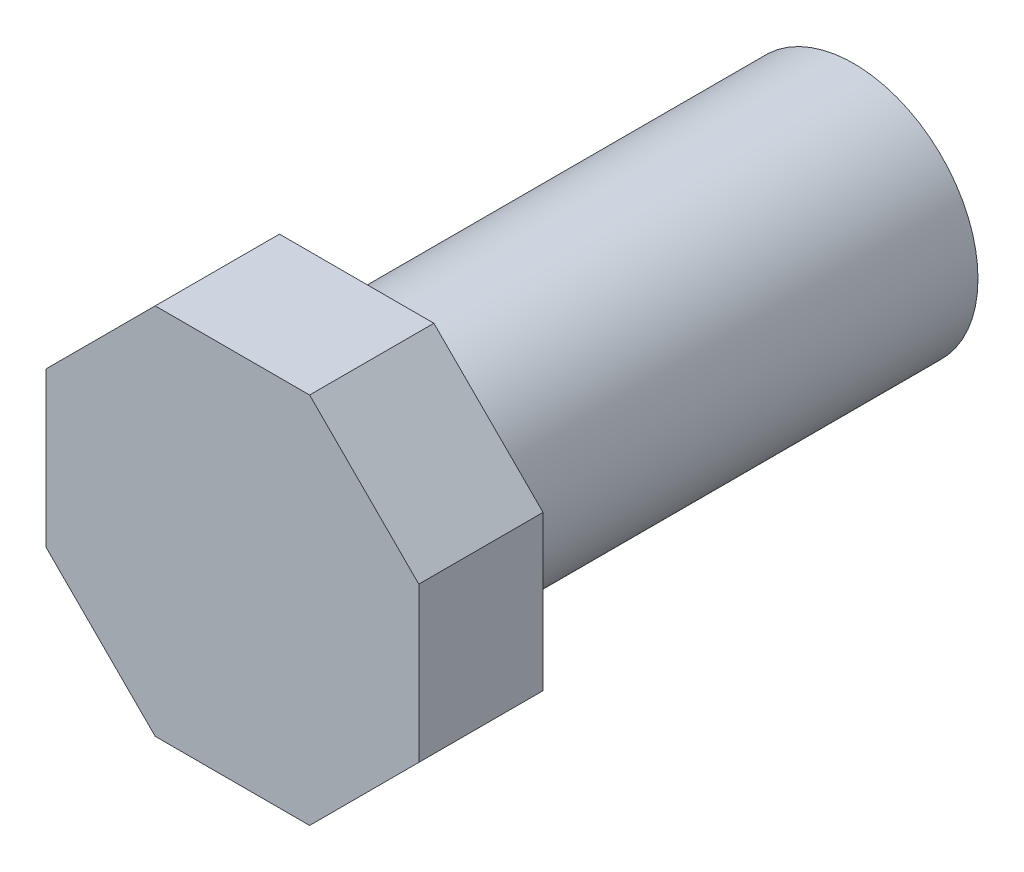
SolidWorks part; units mm, degrees
ref_plane "Plan de face" through (0, 0, 0) normal (0, 0, 1) x (1, 0, 0)
ref_plane "Plan de dessus" through (0, 0, 0) normal (0, 1, 0) x (1, 0, 0)
ref_plane "Plan de droite" through (0, 0, 0) normal (1, 0, 0) x (0, 0, -1)
sketch "Esquisse1" plane through (0, 0, 0) normal (0, 0, 1) x (1, 0, 0)
  circle A0 centre (0, 0) radius 6.35
extrude "Boss.-Extru.1" add sketch "Esquisse1" along normal blind 25.4
sketch "Esquisse2" plane through (0, 0, 25.4) normal (0, 0, 1) x (1, 0, 0)
  line L0 (55, 0) -> (-55, 0) construction
  line L1 (9.525, 3.9454) -> (3.9454, 9.525)
  line L2 (3.9454, 9.525) -> (-3.9454, 9.525)
  line L3 (-3.9454, 9.525) -> (-9.525, 3.9454)
  line L4 (-9.525, 3.9454) -> (-9.525, -3.9454)
  line L5 (-9.525, -3.9454) -> (-3.9454, -9.525)
  line L6 (-3.9454, -9.525) -> (3.9454, -9.525)
  line L7 (3.9454, -9.525) -> (9.525, -3.9454)
  line L8 (9.525, -3.9454) -> (9.525, 3.9454)
  circle A0 centre (0, 0) radius 9.525 construction
  dimension "D1" = 19.05
extrude "Boss.-Extru.2" add sketch "Esquisse2" along normal blind 6.35
